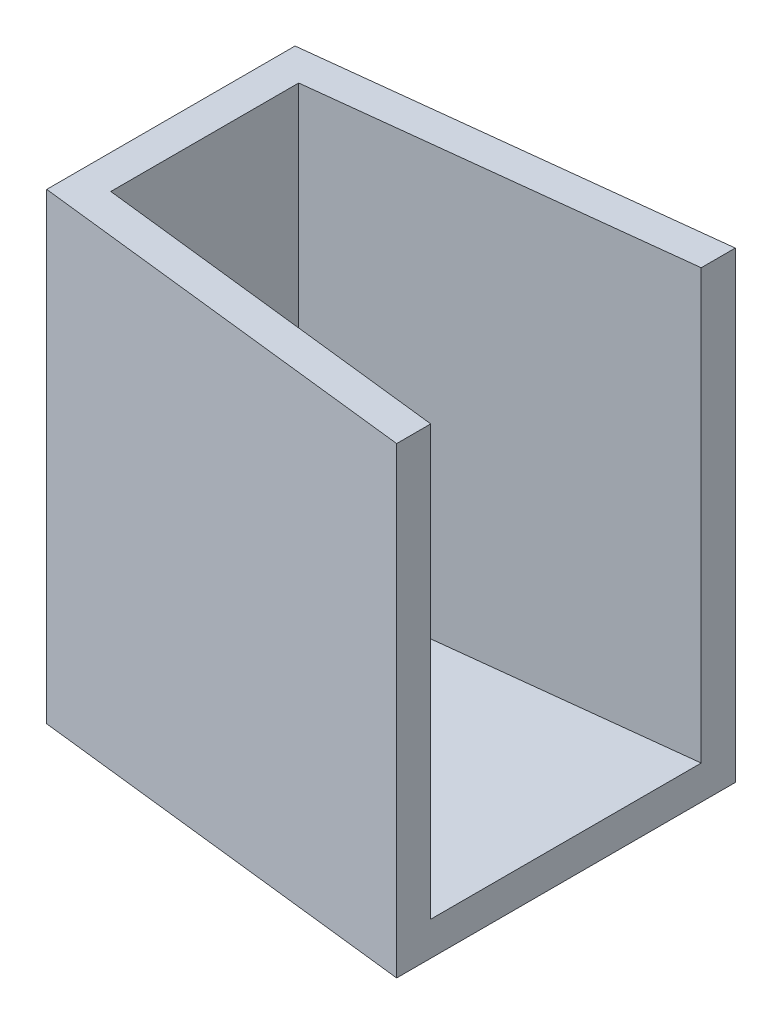
SolidWorks part; units mm, degrees
ref_plane "Front Plane" through (0, 0, 0) normal (0, 0, 1) x (1, 0, 0)
ref_plane "Top Plane" through (0, 0, 0) normal (0, 1, 0) x (1, 0, 0)
ref_plane "Right Plane" through (0, 0, 0) normal (1, 0, 0) x (0, 0, -1)
sketch "Sketch1" plane through (0, 0, 0) normal (0, 1, 0) x (1, 0, 0)
  line L0 (0, -15) -> (0, 15)
  line L1 (0, 0) -> (-35, 0)
  line L2 (-35, -11) -> (-35, 11)
  line L3 (-35, 11) -> (0, 15)
  line L4 (-35, -11) -> (0, -15)
  point P4 (0, 0)
  point P10 (-35, 0)
  dimension "D1" = 35
  dimension "D2" = 22
  dimension "D3" = 30
extrude "Boss-Extrude1" add sketch "Sketch1" along normal blind 3 contours L3 L2 L1 L0 | L2 L4 L0 L1
sketch "Sketch2" plane through (0, 3, 0) normal (0, 1, 0) x (1, 0, 0)
  line L0 (-35, -11) -> (0, -15) construction
  line L1 (0, -15) -> (0, 15) construction
  line L2 (-35, 11) -> (0, 15) construction
  line L3 (-35, -11) -> (-35, 11) construction
  line L4 (-35, -11) -> (0, -15)
  line L5 (0, -15) -> (0, 15)
  line L6 (-35, 11) -> (0, 15)
  line L7 (-35, -11) -> (-35, 11)
  line L8 (-32, 8.3233) -> (0, 11.9805)
  line L10 (-32, -8.3233) -> (0, -11.9805)
  line L11 (-32, -8.3233) -> (-32, 8.3233)
  line L12 (-32, 8.3233) -> (-3, 11.6376) construction
  line L13 (-32, -8.3233) -> (-3, -11.6376) construction
  line L14 (-3, -11.6376) -> (-3, 11.6376) construction
  line M5 (0, 15) -> (-35, 11)
  line M6 (-35, 11) -> (-35, -11)
  line M7 (-35, -11) -> (0, -15)
  line M8 (0, -15) -> (0, 15)
  dimension "D1" = 3
extrude "Boss-Extrude3" add sketch "Sketch2" along normal blind 38 contours L10 L11 L8 L5 M5 M6 M7 M8
